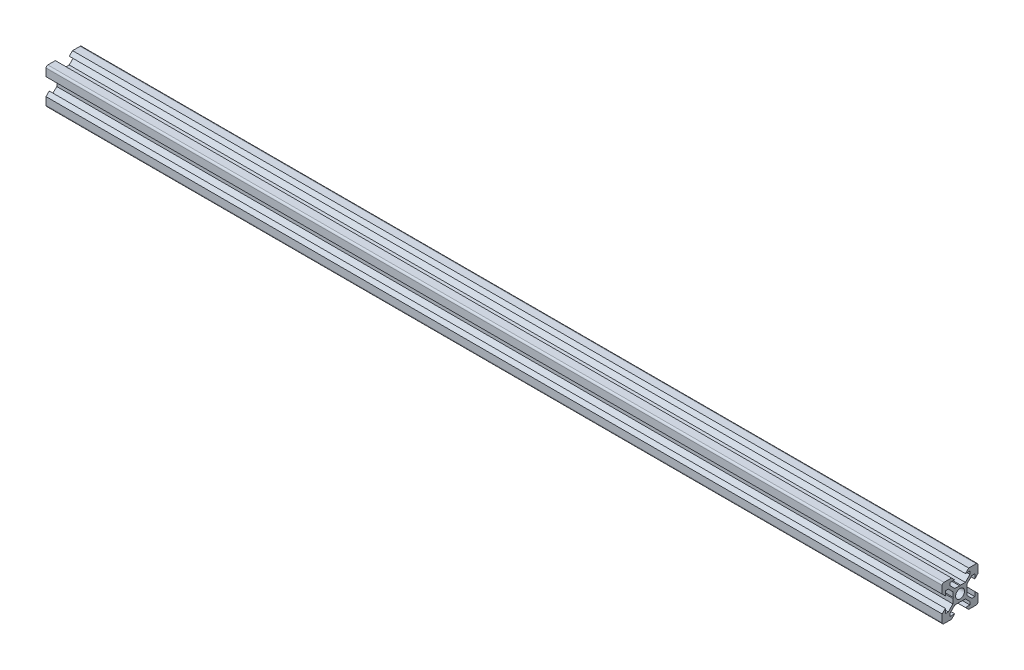
SolidWorks part; units mm, degrees
material "6063-T5"
material "6063-T5"
ref_plane "Plano frontal" through (0, 0, 0) normal (0, 0, 1) x (1, 0, 0)
ref_plane "Plano superior" through (0, 0, 0) normal (0, 1, 0) x (1, 0, 0)
ref_plane "Plano direito" through (0, 0, 0) normal (1, 0, 0) x (0, 0, -1)
sketch "Esboço1" plane through (0, 0, 0) normal (0, 0, 1) x (1, 0, 0)
  line L0 (0, 0) -> (500, 0)
  dimension "D1" = 500
other " C:\\USERS\\USER\\GOOGLE DRIVE\\13. INFORMAÇÕES TÉCNICAS\\BIBLIOTECA SERVIDOR\\PERFIS DE SOLDAGEM\\PERFIL ALUMÍNIO\\QUADRADO\\PF20-11 - PERFIL 2020 V-SLOT - IS MISSING(1)"
ref_plane "Plano1" through (0, 0, 0) normal (1, 0, 0) x (0, 1, 0)
sketch "Sketch11" plane through (0, 0, 0) normal (1, 0, 0) x (0, 1, 0)
  line L0 (-4.8, 10) -> (-3, 8.2)
  line L1 (-3, 8.2) -> (-5.5, 8.2)
  line L2 (-5.5, 8.2) -> (-5.5, 6.5607)
  line L3 (-5.5, 6.5607) -> (-2.9393, 4)
  line L4 (-2.9393, 4) -> (-0.3, 4)
  line L5 (5.5, 6.5607) -> (2.9393, 4)
  line L6 (5.5, 8.2) -> (5.5, 6.5607)
  line L7 (3, 8.2) -> (5.5, 8.2)
  line L8 (4.8, 10) -> (3, 8.2)
  line L9 (-0.3, 4) -> (0, 3.7)
  line L10 (0.3, 4) -> (0, 3.7)
  line L11 (0.3, 4) -> (2.9393, 4)
  line L12 (9, 10) -> (4.8, 10)
  line L13 (10, 4.8) -> (8.2, 3)
  line L14 (10, 4.8) -> (10, 9)
  line L15 (8.2, 3) -> (8.2, 5.5)
  line L16 (8.2, 5.5) -> (6.5607, 5.5)
  line L17 (6.5607, 5.5) -> (4, 2.9393)
  line L18 (4.8, -10) -> (3, -8.2)
  line L19 (3, -8.2) -> (5.5, -8.2)
  line L20 (5.5, -8.2) -> (5.5, -6.5607)
  line L21 (5.5, -6.5607) -> (2.9393, -4)
  line L22 (2.9393, -4) -> (0.3, -4)
  line L23 (0.3, -4) -> (0, -3.7)
  line L24 (-0.3, -4) -> (0, -3.7)
  line L25 (-0.3, -4) -> (-2.9393, -4)
  line L26 (-5.5, -6.5607) -> (-2.9393, -4)
  line L27 (-5.5, -8.2) -> (-5.5, -6.5607)
  line L28 (-3, -8.2) -> (-5.5, -8.2)
  line L29 (-4.8, -10) -> (-3, -8.2)
  line L30 (-10, -4.8) -> (-10, -9)
  line L31 (-10, -4.8) -> (-8.2, -3)
  line L32 (-8.2, -3) -> (-8.2, -5.5)
  line L33 (-8.2, -5.5) -> (-6.5607, -5.5)
  line L34 (-6.5607, -5.5) -> (-4, -2.9393)
  line L35 (-4, -2.9393) -> (-4, -0.3)
  line L36 (-4, -0.3) -> (-3.7, 0)
  line L37 (-4, 0.3) -> (-3.7, 0)
  line L38 (-4, 0.3) -> (-4, 2.9393)
  line L39 (-6.5607, 5.5) -> (-4, 2.9393)
  line L40 (-8.2, 5.5) -> (-6.5607, 5.5)
  line L41 (-8.2, 3) -> (-8.2, 5.5)
  line L42 (-10, 4.8) -> (-8.2, 3)
  line L43 (-4.8, 10) -> (-9, 10)
  line L44 (4, 2.9393) -> (4, 0.3)
  line L45 (4, 0.3) -> (3.7, 0)
  line L46 (4, -0.3) -> (3.7, 0)
  line L47 (4, -0.3) -> (4, -2.9393)
  line L48 (6.5607, -5.5) -> (4, -2.9393)
  line L49 (8.2, -5.5) -> (6.5607, -5.5)
  line L50 (8.2, -3) -> (8.2, -5.5)
  line L51 (10, -4.8) -> (8.2, -3)
  line L52 (10, -9) -> (10, -4.8)
  line L53 (4.8, -10) -> (9, -10)
  line L106 (-10, 9) -> (-10, 4.8)
  line L107 (-9, -10) -> (-4.8, -10)
  arc A0 (10, 9) -> (9, 10) centre (9, 9) ccw
  arc A1 (9, -10) -> (10, -9) centre (9, -9) ccw
  arc A3 (-10, -9) -> (-9, -10) centre (-9, -9) ccw
  arc A4 (-9, 10) -> (-10, 9) centre (-9, 9) ccw
  circle A7 centre (0, 0) radius 2.5
  point P1 (-10, 10)
  point P3 (10, 10)
  point P4 (10, -10)
  point P68 (0, 0)
  point P70 (10, 0)
  point P71 (0, 0)
  point P72 (0, 0)
  point P113 (0, -10)
  point P114 (-10, -10)
  point P115 (-10, 0)
  point P116 (0, 10)
  point P118 (0, 0)
